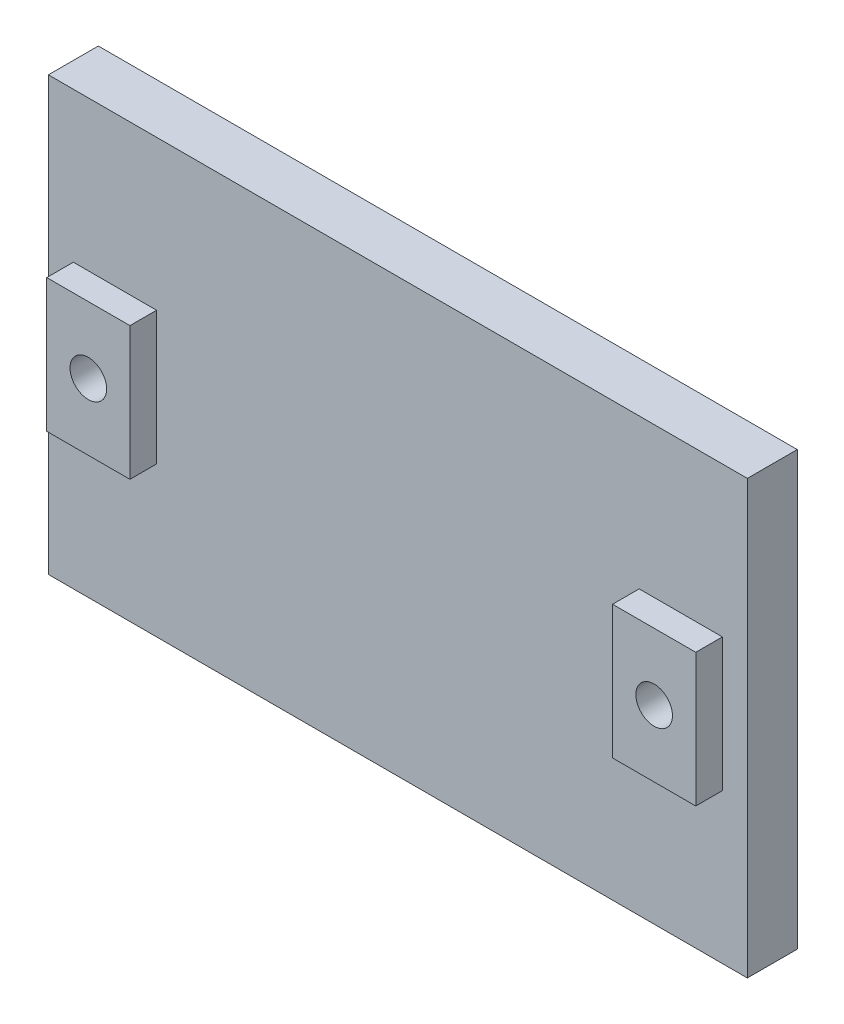
SolidWorks part; units mm, degrees
other "Chassis Accelerometer Mount"
ref_plane "Front Plane" through (0, 0, 0) normal (0, 0, 1) x (1, 0, 0)
ref_plane "Top Plane" through (0, 0, 0) normal (0, 1, 0) x (1, 0, 0)
ref_plane "Right Plane" through (0, 0, 0) normal (1, 0, 0) x (0, 0, -1)
sketch3d "Mounting Plate Sketch datum points"
  point P0 (0, 0, 0)
  point P1 (10, 0, 0)
  point P2 (0, 10, 0)
ref_plane "Mounting Plate Sketch plane" through (0, 0, 0) normal (0, 0, 1) x (1, 0, 0)
sketch "Mounting Plate Sketch" plane through (0, 0, 0) normal (0, 0, 1) x (1, 0, 0)
  line L0 (-21, -13) -> (21, -13)
  line L1 (21, -13) -> (21, 13)
  line L2 (21, 13) -> (-21, 13)
  line L3 (-21, 13) -> (-21, -13)
extrude "Mounting Plate" add sketch "Mounting Plate Sketch" along normal blind 3 separate body
sketch3d "Clamp Seat 1 Sketch datum points"
  point P0 (0, 0, 2.9)
  point P1 (10, 0, 2.9)
  point P2 (0, 10, 2.9)
ref_plane "Clamp Seat 1 Sketch plane" through (0, 0, 2.9) normal (0, 0, 1) x (1, 0, 0)
sketch "Clamp Seat 1 Sketch" plane through (0, 0, 2.9) normal (0, 0, 1) x (1, 0, 0)
  line L0 (-19.5, -4) -> (-14.5, -4)
  line L1 (-14.5, -4) -> (-14.5, 4)
  line L2 (-14.5, 4) -> (-19.5, 4)
  line L3 (-19.5, 4) -> (-19.5, -4)
extrude "Clamp Seat 1" add sketch "Clamp Seat 1 Sketch" along normal blind 1.7
sketch3d "M2 Screw Clearance 1 Sketch datum points"
  point P0 (0, 0, -0.1)
  point P1 (10, 0, -0.1)
  point P2 (0, 10, -0.1)
ref_plane "M2 Screw Clearance 1 Sketch plane" through (0, 0, -0.1) normal (0, 0, 1) x (1, 0, 0)
sketch "M2 Screw Clearance 1 Sketch" plane through (0, 0, -0.1) normal (0, 0, 1) x (1, 0, 0)
  circle A0 centre (-17, 0) radius 1.1
extrude "M2 Screw Clearance 1" cut sketch "M2 Screw Clearance 1 Sketch" along normal blind 4.8
sketch3d "M2 Insert Pocket 1 Sketch datum points"
  point P0 (0, 0, -0.1)
  point P1 (10, 0, -0.1)
  point P2 (0, 10, -0.1)
ref_plane "M2 Insert Pocket 1 Sketch plane" through (0, 0, -0.1) normal (0, 0, 1) x (1, 0, 0)
sketch "M2 Insert Pocket 1 Sketch" plane through (0, 0, -0.1) normal (0, 0, 1) x (1, 0, 0)
  circle A0 centre (-17, 0) radius 1.6
extrude "M2 Insert Pocket 1" cut sketch "M2 Insert Pocket 1 Sketch" along normal blind 2.5
sketch3d "Clamp Seat 2 Sketch datum points"
  point P0 (0, 0, 2.9)
  point P1 (10, 0, 2.9)
  point P2 (0, 10, 2.9)
ref_plane "Clamp Seat 2 Sketch plane" through (0, 0, 2.9) normal (0, 0, 1) x (1, 0, 0)
sketch "Clamp Seat 2 Sketch" plane through (0, 0, 2.9) normal (0, 0, 1) x (1, 0, 0)
  line L0 (14.5, -4) -> (19.5, -4)
  line L1 (19.5, -4) -> (19.5, 4)
  line L2 (19.5, 4) -> (14.5, 4)
  line L3 (14.5, 4) -> (14.5, -4)
extrude "Clamp Seat 2" add sketch "Clamp Seat 2 Sketch" along normal blind 1.7
sketch3d "M2 Screw Clearance 2 Sketch datum points"
  point P0 (0, 0, -0.1)
  point P1 (10, 0, -0.1)
  point P2 (0, 10, -0.1)
ref_plane "M2 Screw Clearance 2 Sketch plane" through (0, 0, -0.1) normal (0, 0, 1) x (1, 0, 0)
sketch "M2 Screw Clearance 2 Sketch" plane through (0, 0, -0.1) normal (0, 0, 1) x (1, 0, 0)
  circle A0 centre (17, 0) radius 1.1
extrude "M2 Screw Clearance 2" cut sketch "M2 Screw Clearance 2 Sketch" along normal blind 4.8
sketch3d "M2 Insert Pocket 2 Sketch datum points"
  point P0 (0, 0, -0.1)
  point P1 (10, 0, -0.1)
  point P2 (0, 10, -0.1)
ref_plane "M2 Insert Pocket 2 Sketch plane" through (0, 0, -0.1) normal (0, 0, 1) x (1, 0, 0)
sketch "M2 Insert Pocket 2 Sketch" plane through (0, 0, -0.1) normal (0, 0, 1) x (1, 0, 0)
  circle A0 centre (17, 0) radius 1.6
extrude "M2 Insert Pocket 2" cut sketch "M2 Insert Pocket 2 Sketch" along normal blind 2.5
